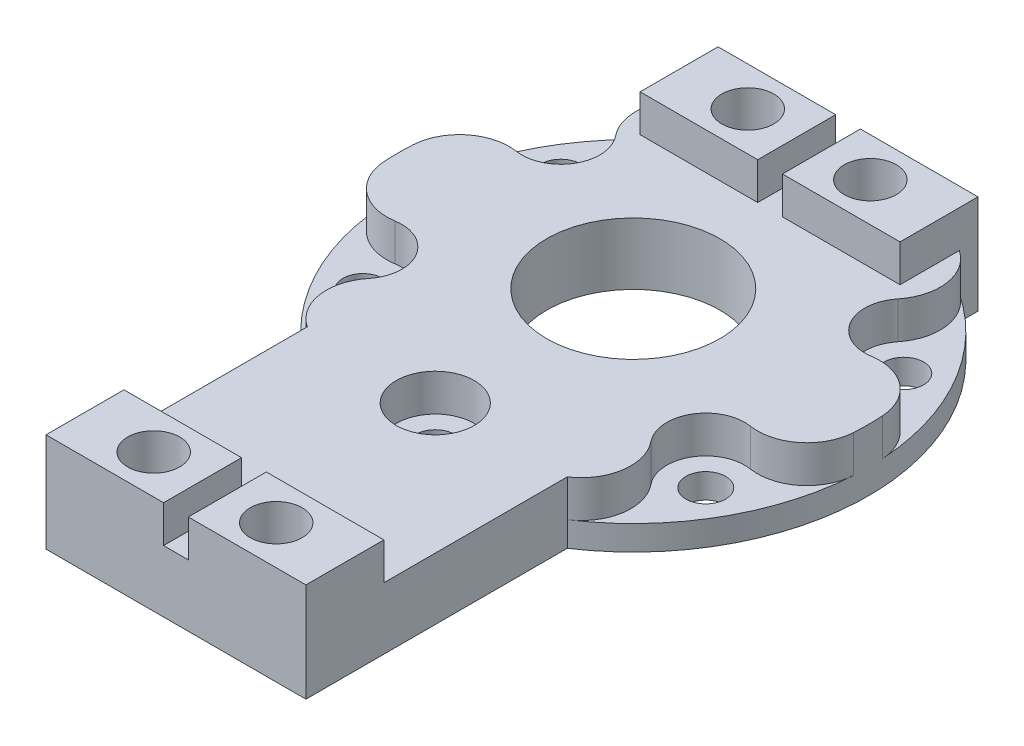
SolidWorks part; units mm, degrees
ref_plane "Front Plane" through (0, 0, 0) normal (0, 0, 1) x (1, 0, 0)
ref_plane "Top Plane" through (0, 0, 0) normal (0, 1, 0) x (1, 0, 0)
ref_plane "Right Plane" through (0, 0, 0) normal (1, 0, 0) x (0, 0, -1)
sketch "Sketch1" plane through (0, 0, 0) normal (0, 1, 0) x (1, 0, 0)
  line L0 (0, 10.45) -> (0, -30.05) construction
  line L1 (-10.5, 10.45) -> (10.5, 10.45) construction
  line L2 (-10.5, -15.8351) -> (-10.5, -30.05) construction
  line L3 (-10.5, -30.05) -> (10.5, -30.05) construction
  line L4 (10.5, 10.45) -> (10.5, -9.8) construction
  line L5 (-10.5, 12.0727) -> (-10.5, 15.8351) construction
  line L6 (-10.5, -9.8) -> (10.5, -9.8) construction
  line L7 (10.5, -36.95) -> (-10.5, -36.95)
  line L8 (10.5, -36.95) -> (10.5, -15.8351)
  line L9 (10.5, 17.35) -> (-10.5, 17.35)
  line L10 (-10.5, -36.95) -> (-10.5, -15.8351)
  line L11 (-10.5, 15.8351) -> (-10.5, 17.35)
  line L12 (-10.5, 10.45) -> (-10.5, 12.0727) construction
  line L13 (-10.5, 10.45) -> (-10.5, -9.8) construction
  line L14 (-10.5, -9.8) -> (-10.5, 10.45) construction
  line L15 (-10.5, -9.8) -> (-10.5, -12.0727) construction
  line L16 (-10.5, -12.0727) -> (-10.5, -9.8) construction
  line L17 (-10.5, -12.0727) -> (-10.5, -15.8351) construction
  line L18 (-10.5, -15.8351) -> (-10.5, -12.0727) construction
  line L19 (10.5, -15.8351) -> (10.5, -12.0727) construction
  line L20 (10.5, 10.45) -> (10.5, 12.0727) construction
  line L21 (10.5, -12.0727) -> (10.5, -15.8351) construction
  line L22 (10.5, -15.8351) -> (10.5, -30.05) construction
  line L23 (10.5, -9.8) -> (10.5, -12.0727) construction
  line L24 (10.5, -12.0727) -> (10.5, -9.8) construction
  line L25 (10.5, -9.8) -> (10.5, 10.45) construction
  line L26 (10.5, 12.0727) -> (10.5, 15.8351) construction
  line L27 (10.5, 15.8351) -> (10.5, 17.35)
  line L28 (0, 17.35) -> (0, -36.95) construction
  line L29 (-4.95, 14.2) -> (-4.95, -33.8) construction
  circle A0 centre (0, 0) radius 16 construction
  circle A1 centre (0, 16) radius 1.6 construction
  circle A2 centre (13.8564, 8) radius 1.6
  circle A3 centre (13.8564, -8) radius 1.6
  circle A4 centre (0, -16) radius 1.6
  circle A5 centre (-13.8564, -8) radius 1.6
  circle A6 centre (-13.8564, 8) radius 1.6
  circle A7 centre (-4.95, 14.2) radius 2.1
  circle A8 centre (4.95, 14.2) radius 2.1
  circle A9 centre (4.95, -33.8) radius 2.1
  circle A10 centre (-4.95, -33.8) radius 2.1
  circle A11 centre (0, 0) radius 7
  arc A12 (-10.5, 15.8351) -> (-10.5, -15.8351) centre (0, 0) ccw
  arc A13 (7.7445, 17.35) -> (-7.7445, 17.35) centre (0, 0) ccw construction
  arc A14 (10.5, 15.8351) -> (7.7445, 17.35) centre (0, 0) ccw construction
  arc A15 (-7.7445, 17.35) -> (-10.5, 15.8351) centre (0, 0) ccw construction
  arc A16 (0, -19) -> (10.5, -15.8351) centre (0, 0) ccw construction
  arc A17 (10.5, -15.8351) -> (10.5, 15.8351) centre (0, 0) ccw
  arc A18 (-4.95, -18.3439) -> (0, -19) centre (0, 0) ccw construction
  arc A19 (-10.5, -15.8351) -> (-4.95, -18.3439) centre (0, 0) ccw construction
  point P46 (0, -9.8)
  point P47 (0, -9.8)
  point P48 (10.5, -2.1116)
  dimension "D1" = 32
  dimension "D3" = 3.2
  dimension "D4" = 4.2
  dimension "D5" = 9.9
  dimension "D6" = 48
  dimension "D10" = 14
  dimension "D11" = 54.3
  dimension "D12" = 3
  dimension "D7" = 40.5
  dimension "D8" = 21
  dimension "D9" = 14.2
  dimension "D2" = 6
extrude "Boss-Extrude1" add sketch "Sketch1" along normal blind 5
sketch "Sketch2" plane through (0, 5, 0) normal (0, 1, 0) x (1, 0, 0)
  circle A0 centre (-13.8564, 8) radius 3.15
  circle A1 centre (0, 16) radius 3.15 construction
  circle A2 centre (13.8564, 8) radius 3.15
  circle A3 centre (13.8564, -8) radius 3.15
  circle A4 centre (0, -16) radius 3.15
  circle A5 centre (-13.8564, -8) radius 3.15
  point P3 (0, 0)
  point P4 (13.8564, 8)
  point P16 (0, 0)
  dimension "D2" = 6.3
  dimension "D1" = 6
extrude "Cut-Extrude1" cut sketch "Sketch2" against normal blind 3
sketch "Sketch3" plane through (0, 5, 0) normal (0, 1, 0) x (1, 0, 0)
  line L0 (10.5, -36.95) -> (10.5, -15.8351) construction
  line L1 (-10.5, 17.35) -> (-1, 17.35)
  line L2 (-10.5, 17.35) -> (-10.5, 11.05)
  line L3 (-10.5, 11.05) -> (-1, 11.05)
  line L4 (10.5, 17.35) -> (10.5, 11.05)
  line L5 (0, 11.05) -> (0, 17.35) construction
  line L6 (1, 11.05) -> (1, 17.35)
  line L7 (-1, 11.05) -> (-1, 17.35)
  line L8 (0, 17.35) -> (1, 17.35) construction
  line L9 (1, 17.35) -> (10.5, 17.35)
  line L10 (-1, 17.35) -> (0, 17.35) construction
  line L11 (0, 11.05) -> (1, 11.05) construction
  line L12 (1, 11.05) -> (10.5, 11.05)
  line L13 (-1, 11.05) -> (0, 11.05) construction
  line L14 (10.5, 17.35) -> (-10.5, 17.35) construction
  line L15 (10.5, -9.8) -> (-10.5, -9.8) construction
  line L17 (-1, -30.65) -> (0, -30.65) construction
  line L18 (0, -30.65) -> (1, -30.65) construction
  line L19 (-1, -36.95) -> (0, -36.95) construction
  line L20 (0, -36.95) -> (1, -36.95) construction
  line L21 (0, -30.65) -> (0, -36.95) construction
  line L22 (1, -30.65) -> (10.5, -30.65)
  line L23 (1, -36.95) -> (10.5, -36.95)
  line L24 (-1, -30.65) -> (-1, -36.95)
  line L25 (1, -30.65) -> (1, -36.95)
  line L26 (10.5, -36.95) -> (10.5, -30.65)
  line L27 (-10.5, -30.65) -> (-1, -30.65)
  line L28 (-10.5, -36.95) -> (-10.5, -30.65)
  line L29 (-10.5, -36.95) -> (-1, -36.95)
  line L30 (-10.5, 17.35) -> (-10.5, 15.8351) construction
  line L31 (-10.5, -15.8351) -> (-10.5, -36.95) construction
  line L32 (10.5, -36.95) -> (10.5, -15.8351) construction
  circle A1 centre (4.95, -33.8) radius 2.1
  circle A2 centre (4.95, -33.8) radius 2.1
  circle A3 centre (-4.95, -33.8) radius 2.1
  circle A4 centre (-4.95, -33.8) radius 2.1
  circle A5 centre (4.95, 14.2) radius 2.1
  circle A6 centre (4.95, 14.2) radius 2.1
  circle A7 centre (-4.95, 14.2) radius 2.1
  circle A8 centre (-4.95, 14.2) radius 2.1
  point P7 (-4.95, 14.2)
  point P10 (-10.5, 14.2)
  point P20 (-10.5, -19.802)
  point P32 (-4.95, -33.8)
  point P33 (0, 0)
  point P34 (-10.5, 17.35)
  point P49 (0, 0)
  point P50 (-5.75, -66.9851)
  point P51 (0, 0)
  point P53 (10.5, -21.0112)
  point P56 (-4.95, -33.8)
  dimension "D1" = 1
  dimension "D2" = 1
  dimension "D3" = 0
  dimension "D4" = 0
  dimension "D5" = 0
  dimension "D6" = 0
extrude "Boss-Extrude2" add sketch "Sketch3" along normal blind 3
fillet "Fillet2" radius 4 8 edges at (15.9064, 3.5, 10.3917) (16.9526, 3.5, 8.5795) (15.9064, 3.5, -10.3917) (16.9526, 3.5, -8.5795) (-16.9526, 3.5, 8.5795) (-15.9064, 3.5, 10.3917) (-16.9526, 3.5, -8.5795) (-15.9064, 3.5, -10.3917)
